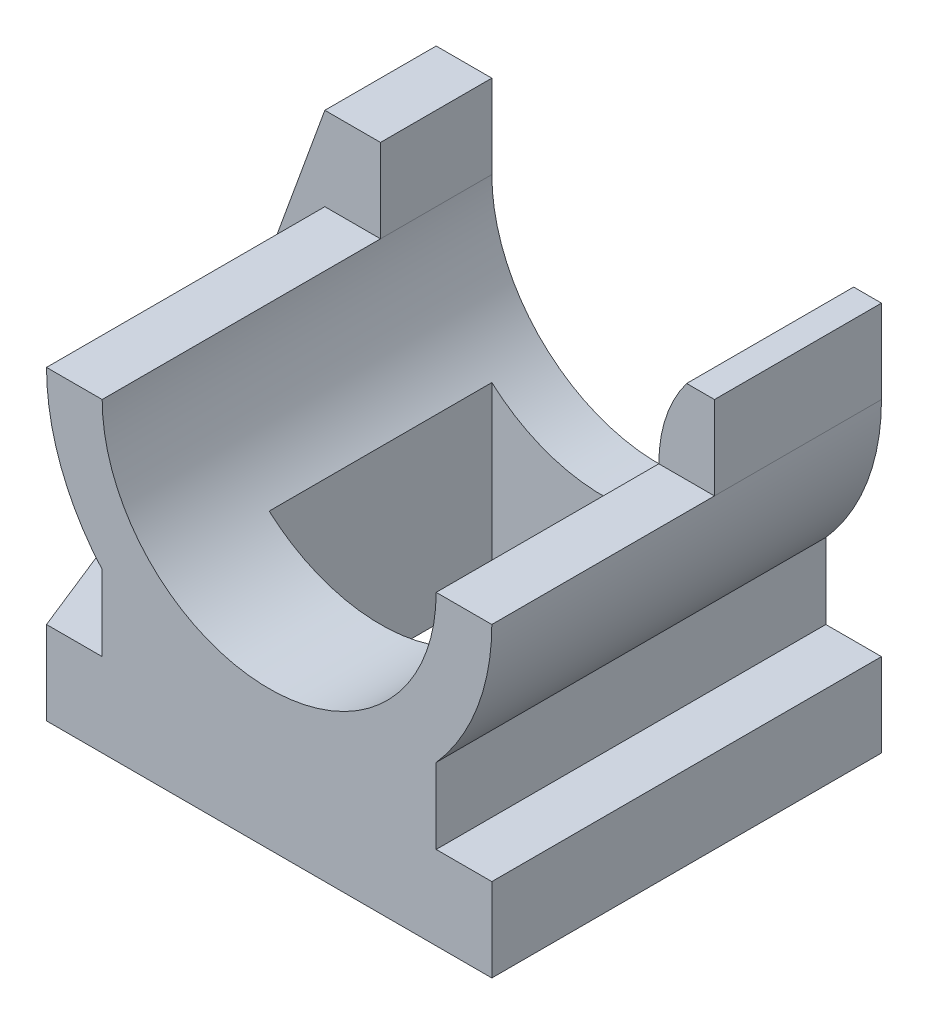
SolidWorks part; units mm, degrees
ref_plane "Front Plane" through (0, 0, 0) normal (0, 0, 1) x (1, 0, 0)
ref_plane "Top Plane" through (0, 0, 0) normal (0, 1, 0) x (1, 0, 0)
ref_plane "Right Plane" through (0, 0, 0) normal (1, 0, 0) x (0, 0, -1)
sketch "Sketch1" plane through (0, 0, 0) normal (0, 1, 0) x (1, 0, 0)
  line L0 (-60, 0) -> (40, 0)
  line L1 (40, 0) -> (40, -70)
  line L2 (40, -70) -> (-40, -70)
  line L3 (-40, -70) -> (-60, -20)
  line L4 (-60, -20) -> (-60, 0)
  dimension "D1" = 100
  dimension "D2" = 70
  dimension "D3" = 80
  dimension "D4" = 20
  dimension "D5" = 40
extrude "Boss-Extrude1" add sketch "Sketch1" along normal blind 15
sketch "Sketch2" plane through (0, 0, 0) normal (0, 0, 1) x (1, 0, 0)
  line L0 (-30, 10) -> (30, 10)
  line L1 (30, 10) -> (30, 28.5425)
  line L2 (40, 55) -> (-40, 55)
  line L3 (-30, 28.5425) -> (-30, 10)
  arc A0 (30, 28.5425) -> (40, 55) centre (0, 55) ccw
  arc A1 (-40, 55) -> (-30, 28.5425) centre (0, 55) ccw
  dimension "D1" = 80
  dimension "D2" = 60
  dimension "D3" = 55
  dimension "D4" = 30
extrude "Boss-Extrude2" add sketch "Sketch2" along normal blind 70
sketch "Sketch3" plane through (0, 0, 0) normal (0, 0, 1) x (1, 0, 0)
  line L0 (-60, 15) -> (-30, 15)
  line L1 (-30, 15) -> (-30, 70)
  line L2 (-30, 70) -> (-40, 70)
  line L3 (-40, 70) -> (-60, 15)
  dimension "D1" = 10
  dimension "D2" = 30
  dimension "D3" = 70
  dimension "D4" = 15
  dimension "D5" = 30
extrude "Boss-Extrude3" add sketch "Sketch3" along normal blind 20
sketch "Sketch4" plane through (0, 0, 0) normal (0, 0, 1) x (1, 0, 0)
  line L0 (30, 55) -> (40, 55)
  line L1 (40, 55) -> (40, 70)
  line L2 (40, 70) -> (35, 70)
  arc A0 (35, 70) -> (30, 55) centre (55, 55) ccw
  dimension "D1" = 15
  dimension "D2" = 10
  dimension "D3" = 5
  dimension "D4" = 40
  dimension "D5" = 55
extrude "Boss-Extrude4" add sketch "Sketch4" along normal blind 30
sketch "Sketch5" plane through (0, 0, 0) normal (0, 0, 1) x (1, 0, 0)
  line L0 (-30, 55) -> (30, 55)
  arc A0 (-30, 55) -> (30, 55) centre (0, 55) ccw
  dimension "D1" = 60
  dimension "D2" = 55
extrude "Cut-Extrude1" cut sketch "Sketch5" along normal through all
sketch "Sketch6" plane through (0, 0, 0) normal (0, 1, 0) x (1, 0, 0)
  line L1 (-20, -10) -> (20, -10)
  line L2 (-20, -10) -> (-20, -50)
  line L3 (-20, -50) -> (20, -50)
  line L4 (20, -10) -> (20, -50)
  dimension "D1" = 40
  dimension "D2" = 40
  dimension "D3" = 10
  dimension "D4" = 20
extrude "Cut-Extrude2" cut sketch "Sketch6" along normal through all
